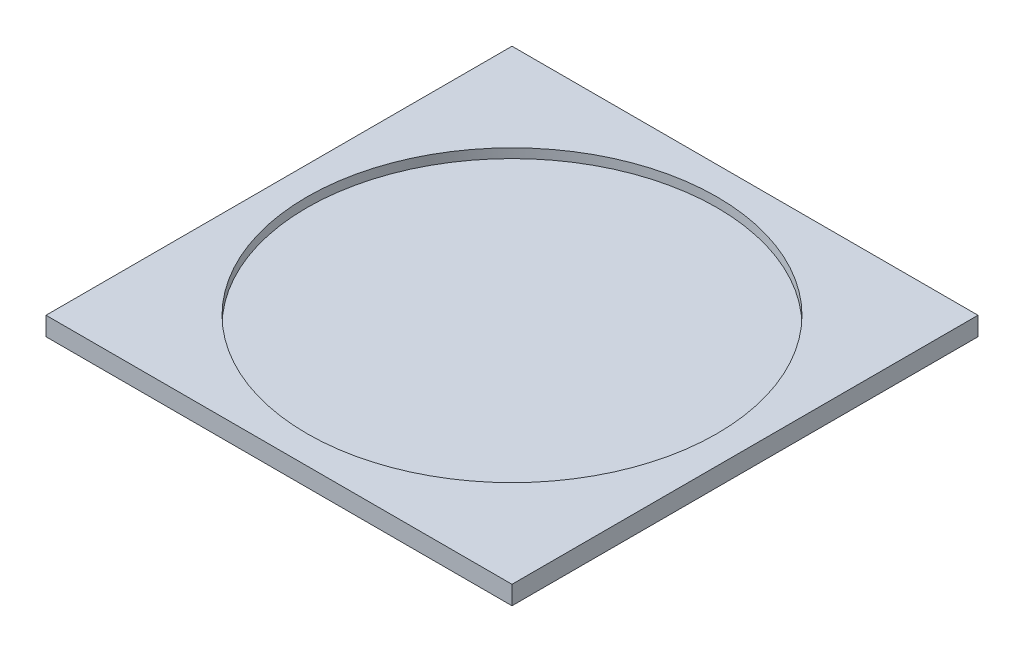
SolidWorks part; units mm, degrees
ref_plane "Front Plane" through (0, 0, 0) normal (0, 0, 1) x (1, 0, 0)
ref_plane "Top Plane" through (0, 0, 0) normal (0, 1, 0) x (1, 0, 0)
ref_plane "Right Plane" through (0, 0, 0) normal (1, 0, 0) x (0, 0, -1)
sketch "Sketch1" plane through (0, 0, 0) normal (0, 1, 0) x (1, 0, 0)
  line L1 (-125, -125) -> (125, -125)
  line L2 (-125, -125) -> (-125, 125)
  line L3 (-125, 125) -> (125, 125)
  line L4 (125, -125) -> (125, 125)
  line L5 (-125, -125) -> (125, 125) construction
  line L6 (-125, 125) -> (125, -125) construction
  point P0 (0, 0)
  dimension "D1" = 250
extrude "Boss-Extrude1" add sketch "Sketch1" along normal blind 10
sketch "Sketch2" plane through (0, 10, 0) normal (0, 1, 0) x (1, 0, 0)
  line L1 (125, 125) -> (-125, 125) construction
  circle A0 centre (0, 0) radius 110
  point P5 (0, 110)
  dimension "D1" = 15
extrude "Cut-Extrude1" cut sketch "Sketch2" against normal blind 5
